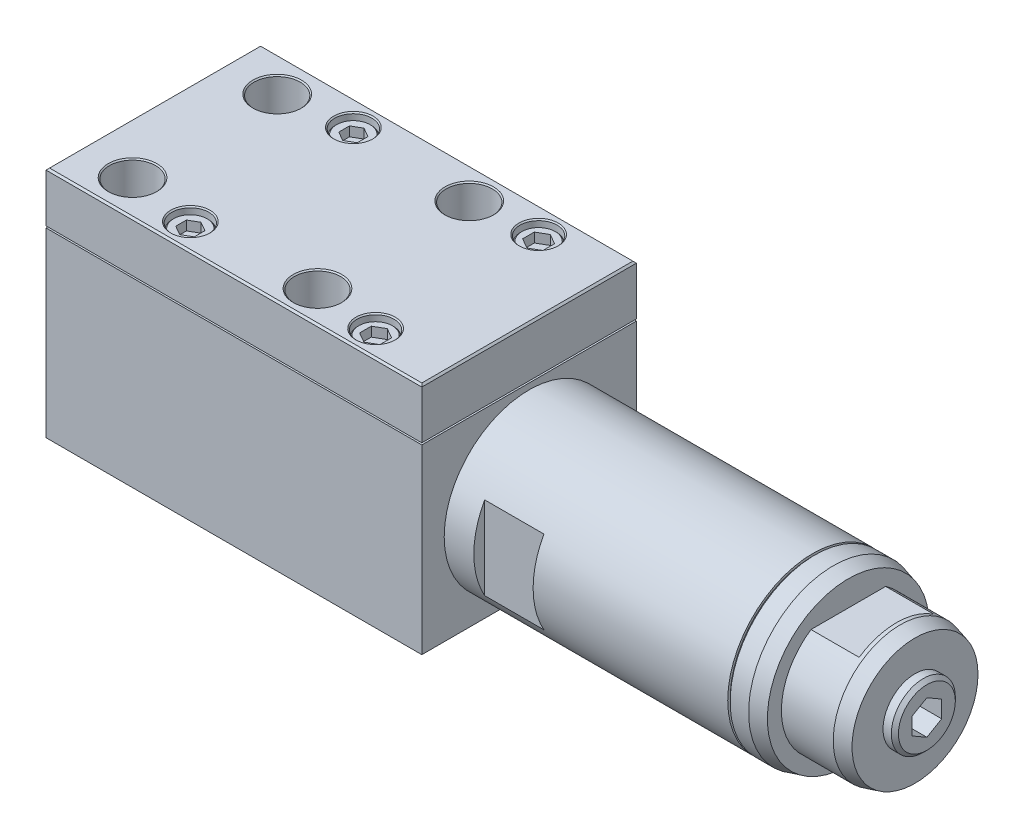
SolidWorks part; units mm, degrees
ref_plane "Front Plane" through (0, 0, 0) normal (0, 0, 1) x (1, 0, 0)
ref_plane "Top Plane" through (0, 0, 0) normal (0, 1, 0) x (1, 0, 0)
ref_plane "Right Plane" through (0, 0, 0) normal (1, 0, 0) x (0, 0, -1)
sketch "Sketch1" plane through (0, 0, 0) normal (0, 0, 1) x (1, 0, 0)
  line L0 (-81.5975, 50.038) -> (-81.5975, 0) construction
  line L1 (-84.1375, 50.038) -> (84.1375, 50.038)
  line L2 (-84.1375, 50.038) -> (-84.1375, 0)
  line L3 (-84.1375, 0) -> (84.1375, 0)
  line L4 (84.1375, 50.038) -> (84.1375, 0)
  line L5 (-1.0795, 50.038) -> (-1.0795, 0) construction
  line L6 (-81.5975, 38.9255) -> (-1.0795, 38.9255) construction
  dimension "D1" = 168.275
  dimension "D2" = 50.038
  dimension "D3" = 2.54
  dimension "D4" = 80.518
  dimension "D5" = 11.1125
sketch "Sketch2" plane through (0, 0, 0) normal (0, 0, 1) x (1, 0, 0)
  line L1 (-81.5975, 38.9255) -> (-1.0795, 38.9255)
  line L2 (-81.5975, 38.9255) -> (-81.5975, 0)
  line L3 (-81.5975, 0) -> (-1.0795, 0)
  line L4 (-1.0795, 38.9255) -> (-1.0795, 0)
extrude "Boss-Extrude1" add sketch "Sketch2" along normal mid plane 45.974
sketch "Sketch3" plane through (0, 38.9255, 0) normal (0, 1, 0) x (1, 0, 0)
  line L4 (-1.0795, 22.987) -> (-81.5975, 22.987)
  line L5 (-81.5975, 22.987) -> (-81.5975, -22.987)
  line L6 (-81.5975, -22.987) -> (-1.0795, -22.987)
  line L7 (-1.0795, -22.987) -> (-1.0795, 22.987)
  line L8 (-1.0795, 22.987) -> (-81.5975, 22.987)
  line L9 (-81.5975, 22.987) -> (-81.5975, -22.987)
  line L10 (-81.5975, -22.987) -> (-1.0795, -22.987)
  line L11 (-1.0795, -22.987) -> (-1.0795, 22.987)
  dimension "D1" = 0
extrude "Boss-Extrude2" add sketch "Sketch3" along normal up to vertex (11.1125 mm away) separate body up to point (-84.1375, 50.038, 0)
chamfer "Chamfer1" distance 0.381 angle 45 8 edges at (-41.3385, 38.9255, -22.987) (-81.5975, 38.9255, 0) (-41.3385, 38.9255, 22.987) (-1.0795, 38.9255, 0) (-41.3385, 50.038, 22.987) (-81.5975, 50.038, 0) (-41.3385, 50.038, -22.987) (-1.0795, 50.038, 0)
combine bodies "Combine1" operation type add bodies to combine 101 102
sketch "Sketch4" plane through (0, 50.038, 0) normal (0, 1, 0) x (1, 0, 0)
  line L0 (-70.5485, 15.494) -> (-70.5485, -15.494) construction
  line L1 (-30.1625, 16.256) -> (-30.1625, -16.256) construction
  line L2 (-70.5485, 0) -> (-30.1625, 0) construction
  line L3 (-81.5975, 0) -> (-1.0795, 0) construction
  line L4 (-1.4605, -22.606) -> (-1.4605, 22.606) construction
  circle A0 centre (-70.5485, 15.494) radius 4.953
  circle A1 centre (-30.1625, 16.256) radius 4.953
  circle A2 centre (-70.5485, -15.494) radius 4.953
  circle A3 centre (-30.1625, -16.256) radius 4.953
  dimension "D1" = 9.906
  dimension "D2" = 30.988
  dimension "D3" = 32.512
  dimension "D4" = 69.088
  dimension "D5" = 40.386
extrude "Cut-Extrude1" cut sketch "Sketch4" against normal offset from surface (28.038 mm away) 22 up to face at (-41.3385, 0, 0)
sketch "Sketch5" plane through (0, 50.038, 0) normal (0, 1, 0) x (1, 0, 0)
  line L0 (-56.1975, 17.4625) -> (-56.1975, -17.4625) construction
  line L1 (0, 0) -> (-56.1975, 0) construction
  line L2 (-81.5975, -22.987) -> (-81.5975, 22.987) construction
  circle A0 centre (-56.1975, 17.4625) radius 3.9687
  circle A1 centre (-16.51, 17.4625) radius 3.9688
  circle A2 centre (-56.1975, -17.4625) radius 3.9687
  circle A3 centre (-16.51, -17.4625) radius 3.9688
  dimension "D1" = 7.9375
  dimension "D2" = 34.925
  dimension "D3" = 39.6875
  dimension "D4" = 25.4
extrude "Cut-Extrude2" cut sketch "Sketch5" against normal blind 1.27
chamfer "Chamfer2" distance 0.254 angle 45 8 edges at (-70.5485, 50.038, 20.447) (-70.5485, 50.038, -10.541) (-16.51, 50.038, -13.4937) (-16.51, 50.038, 21.4313) (-30.1625, 50.038, 21.209) (-30.1625, 50.038, -11.303) (-56.1975, 50.038, 21.4313) (-56.1975, 50.038, -13.4937)
sketch "Sketch6" plane through (0, 48.768, 0) normal (0, 1, 0) x (1, 0, 0)
  circle A1 centre (-56.1975, 17.4625) radius 3.9688
  circle A2 centre (-56.1975, 17.4625) radius 3.9687
  circle A3 centre (-16.51, 17.4625) radius 3.9688
  circle A4 centre (-16.51, 17.4625) radius 3.9688
  circle A5 centre (-16.51, -17.4625) radius 3.9688
  circle A6 centre (-16.51, -17.4625) radius 3.9688
  circle A7 centre (-56.1975, -17.4625) radius 3.9688
  circle A8 centre (-56.1975, -17.4625) radius 3.9687
  dimension "D1" = 0
  dimension "D2" = 0
  dimension "D3" = 0
  dimension "D4" = 0
extrude "Cut-Extrude-Thin1" cut sketch "Sketch6" against normal blind 1.27 thin thin type one direction reverse wall 0.127
chamfer "Chamfer3" distance 0.254 angle 45 4 edges at (-12.6683, 48.768, -17.4625) (-12.6682, 48.768, 17.4625) (-52.3558, 48.768, 17.4625) (-52.3558, 48.768, -17.4625)
sketch "Sketch7" plane through (0, 48.768, 0) normal (0, 1, 0) x (1, 0, 0)
  line L1 (-56.1975, 19.7502) -> (-58.1787, 18.6063)
  line L2 (-58.1787, 18.6063) -> (-58.1787, 16.3187)
  line L3 (-58.1787, 16.3187) -> (-56.1975, 15.1748)
  line L4 (-56.1975, 15.1748) -> (-54.2163, 16.3187)
  line L5 (-54.2163, 16.3187) -> (-54.2163, 18.6063)
  line L6 (-54.2163, 18.6063) -> (-56.1975, 19.7502)
  line L7 (-56.1975, -15.1748) -> (-58.1787, -16.3187)
  line L8 (-58.1787, -16.3187) -> (-58.1787, -18.6063)
  line L9 (-58.1787, -18.6063) -> (-56.1975, -19.7502)
  line L10 (-56.1975, -19.7502) -> (-54.2163, -18.6063)
  line L11 (-54.2163, -18.6063) -> (-54.2163, -16.3187)
  line L12 (-54.2163, -16.3187) -> (-56.1975, -15.1748)
  line L13 (-16.51, -14.9588) -> (-18.6783, -16.2107)
  line L14 (-18.6783, -16.2107) -> (-18.6783, -18.7143)
  line L15 (-18.6783, -18.7143) -> (-16.51, -19.9662)
  line L16 (-16.51, -19.9662) -> (-14.3417, -18.7143)
  line L17 (-14.3417, -18.7143) -> (-14.3417, -16.2107)
  line L18 (-14.3417, -16.2107) -> (-16.51, -14.9588)
  line L19 (-16.51, 19.9662) -> (-18.6783, 18.7143)
  line L20 (-18.6783, 18.7143) -> (-18.6783, 16.2107)
  line L21 (-18.6783, 16.2107) -> (-16.51, 14.9588)
  line L22 (-16.51, 14.9588) -> (-14.3417, 16.2107)
  line L23 (-14.3417, 16.2107) -> (-14.3417, 18.7143)
  line L24 (-14.3417, 18.7143) -> (-16.51, 19.9662)
  circle A0 centre (-56.1975, 17.4625) radius 1.9812 construction
  circle A1 centre (-56.1975, -17.4625) radius 1.9812 construction
  circle A2 centre (-16.51, -17.4625) radius 2.1683 construction
  circle A3 centre (-16.51, 17.4625) radius 2.1683 construction
  dimension "D1" = 3.9624
extrude "Cut-Extrude3" cut sketch "Sketch7" against normal blind 2.032
sketch "Sketch8" plane through (0, 50.038, 0) normal (0, 1, 0) x (1, 0, 0)
  circle A0 centre (-70.5485, 15.494) radius 2.75
  circle A1 centre (-30.1625, 16.256) radius 2.75
  circle A2 centre (-30.1625, -16.256) radius 2.75
  circle A3 centre (-70.5485, -15.494) radius 2.75
  dimension "D1" = 5.5
extrude "Cut-Extrude4" cut sketch "Sketch8" against normal through all
sketch "Sketch9" plane through (0, 0, 0) normal (0, -1, 0) x (1, 0, 0)
  line L1 (-70.5485, -15.494) -> (-70.5485, 15.494) construction
  line L3 (-81.5975, 0) -> (-1.0795, 0) construction
  circle A0 centre (-48.9585, 10.414) radius 3.556
  circle A1 centre (-48.9585, -10.414) radius 3.556
  circle A2 centre (-57.8485, 0) radius 3.556
  circle A3 centre (-40.3225, 0) radius 3.556
  circle A4 centre (-37.5285, 15.494) radius 2.159 construction
  circle A5 centre (-70.5485, 15.494) radius 2.75 construction
  dimension "D1" = 7.112
  dimension "D2" = 4.318
  dimension "D8" = 25.908
  dimension "D3" = 33.02
  dimension "D4" = 21.59
  dimension "D5" = 12.7
  dimension "D6" = 30.226
  dimension "D7" = 5.08
extrude "Cut-Extrude5" cut sketch "Sketch9" against normal blind 2.54
sketch "Sketch10" plane through (0, 0, 0) normal (0, -1, 0) x (1, 0, 0)
  circle A0 centre (-37.5285, 15.494) radius 2.159 construction
  circle A1 centre (-37.5285, 15.494) radius 2.159
extrude "Cut-Extrude6" cut sketch "Sketch10" against normal blind 4
sketch "Sketch12" plane through (0, 2.54, 0) normal (0, -1, 0) x (1, 0, 0)
  circle A1 centre (-48.9585, 10.414) radius 3.556
  circle A2 centre (-48.9585, 10.414) radius 3.556
  circle A3 centre (-40.3225, 0) radius 3.556
  circle A4 centre (-40.3225, 0) radius 3.556
  circle A5 centre (-57.8485, 0) radius 3.556
  circle A6 centre (-57.8485, 0) radius 3.556
  circle A7 centre (-48.9585, -10.414) radius 3.556
  circle A8 centre (-48.9585, -10.414) radius 3.556
  dimension "D1" = 0
  dimension "D2" = 0
  dimension "D3" = 0
  dimension "D4" = 0
extrude "Cut-Extrude7" cut sketch "Sketch12" against normal through all draft 45
sketch "Sketch17" plane through (-1.0795, 0, 0) normal (1, 0, 0) x (0, 0, -1)
  line L4 (0, 50.038) -> (0, 0) construction
  line L8 (21.717, 1.27) -> (21.717, 37.6555)
  line L9 (21.717, 37.6555) -> (-21.717, 37.6555)
  line L10 (-21.717, 37.6555) -> (-21.717, 1.27)
  line L11 (-21.717, 1.27) -> (21.717, 1.27)
  line L12 (21.717, 1.27) -> (21.717, 37.6555) construction
  line L13 (21.717, 37.6555) -> (-21.717, 37.6555) construction
  line L14 (-21.717, 37.6555) -> (-21.717, 1.27) construction
  line L15 (-21.717, 1.27) -> (21.717, 1.27) construction
  circle A0 centre (0, 19.4627) radius 18.1928
  dimension "D1" = 1.27
extrude "Boss-Extrude4" add sketch "Sketch17" along normal up to vertex (85.217 mm away) up to point (84.1375, 0, 0)
sketch "Sketch13" plane through (-81.5975, 0, 0) normal (-1, 0, 0) x (0, 0, 1)
  circle A0 centre (0, 19.4627) radius 6.858
  circle A1 centre (0, 19.4627) radius 18.1928 construction
  dimension "D1" = 13.716
extrude "Boss-Extrude3" add sketch "Sketch13" along normal blind 2.54
chamfer "Chamfer4" distance 0.762 angle 45 1 edges at (-84.1375, 19.4627, 6.858)
sketch "Sketch14" plane through (-84.1375, 0, 0) normal (-1, 0, 0) x (0, 0, 1)
  line L1 (0, 23.1289) -> (-3.175, 21.2958)
  line L2 (-3.175, 21.2958) -> (-3.175, 17.6297)
  line L3 (-3.175, 17.6297) -> (0, 15.7966)
  line L4 (0, 15.7966) -> (3.175, 17.6297)
  line L5 (3.175, 17.6297) -> (3.175, 21.2958)
  line L6 (3.175, 21.2958) -> (0, 23.1289)
  circle A0 centre (0, 19.4627) radius 3.175 construction
  dimension "D1" = 6.35
extrude "Cut-Extrude8" cut sketch "Sketch14" against normal blind 5.08
sketch "Sketch15" plane through (-84.1375, 0, 0) normal (-1, 0, 0) x (0, 0, 1)
  circle A0 centre (0, 19.4627) radius 3.6662
extrude "Cut-Extrude9" cut sketch "Sketch15" against normal through all draft 45
sketch "Sketch18" plane through (84.1375, 0, 0) normal (1, 0, 0) x (0, 0, -1)
  circle A0 centre (0, 19.4627) radius 6.858
  dimension "D1" = 13.716
extrude "Cut-Extrude10" cut sketch "Sketch18" against normal blind 2.54 flip side to cut
sketch "Sketch19" plane through (84.1375, 0, 0) normal (1, 0, 0) x (0, 0, -1)
  line L6 (3.175, 21.2958) -> (0, 23.1289)
  line L7 (3.175, 17.6297) -> (3.175, 21.2958)
  line L8 (0, 15.7966) -> (3.175, 17.6297)
  line L9 (-3.175, 17.6297) -> (0, 15.7966)
  line L10 (-3.175, 21.2958) -> (-3.175, 17.6297)
  line L11 (0, 23.1289) -> (-3.175, 21.2958)
  line L12 (3.175, 21.2958) -> (0, 23.1289)
  line L13 (3.175, 17.6297) -> (3.175, 21.2958)
  line L14 (0, 15.7966) -> (3.175, 17.6297)
  line L15 (-3.175, 17.6297) -> (0, 15.7966)
  line L16 (-3.175, 21.2958) -> (-3.175, 17.6297)
  line L17 (0, 23.1289) -> (-3.175, 21.2958)
  dimension "D1" = 0
extrude "Cut-Extrude11" cut sketch "Sketch19" against normal blind 5.08
chamfer "Chamfer5" distance 0.762 angle 45 1 edges at (84.1375, 19.4627, -6.858)
sketch "Sketch20" plane through (0, 0, 0) normal (0, 0, 1) x (1, 0, 0)
  line L0 (81.5975, 32.9565) -> (78.4225, 33.8072)
  line L1 (81.5975, 1.27) -> (81.5975, 37.6555) construction
  line L2 (78.4225, 33.8072) -> (67.31, 33.8072)
  line L3 (67.31, 33.8072) -> (67.31, 36.8048)
  line L4 (67.31, 36.8048) -> (64.135, 37.6555)
  line L5 (81.5975, 37.6555) -> (-1.0795, 37.6555) construction
  line L6 (60.1726, 37.6555) -> (60.1726, 37.1475)
  line L7 (60.1726, 37.1475) -> (59.6646, 37.1475)
  line L8 (59.6646, 37.1475) -> (59.6646, 40.8305)
  line L9 (59.6646, 40.8305) -> (81.5975, 40.8305)
  line L10 (81.5975, 40.8305) -> (81.5975, 32.9565)
  line L11 (83.3755, 19.4627) -> (-1.0795, 19.4627) construction
  line L12 (83.3755, 12.6048) -> (83.3755, 26.3208) construction
  line L13 (60.1726, 37.6555) -> (64.135, 37.6555)
  line L14 (-1.0795, 50.038) -> (-1.0795, 0) construction
  dimension "D1" = 15
  dimension "D2" = 0.508
  dimension "D3" = 0.508
  dimension "D4" = 3.175
  dimension "D5" = 3.9624
  dimension "D6" = 26.9875
  dimension "D7" = 14.2875
  dimension "D8" = 3.175
revolve "Cut-Revolve1" cut sketch "Sketch20" angle 360 about L11
sketch "Sketch21" plane through (67.31, 0, 0) normal (1, 0, 0) x (0, 0, -1)
  line L0 (8.0003, 7.5565) -> (-8.0003, 7.5565)
  line L1 (-8.0003, 31.369) -> (8.0003, 31.369)
  circle A1 centre (0, 19.4627) radius 14.3445 construction
  arc A2 (8.0003, 31.369) -> (-8.0003, 31.369) centre (0, 19.4627) ccw
  circle A3 centre (0, 19.4627) radius 14.3445 construction
  arc A6 (-8.0003, 7.5565) -> (8.0003, 7.5565) centre (0, 19.4627) ccw
  circle A7 centre (0, 19.4627) radius 13.4937 construction
  dimension "D1" = 23.8125
extrude "Cut-Extrude12" cut sketch "Sketch21" along normal blind 10.3124
sketch "Sketch22" plane through (-1.0795, 0, 0) normal (1, 0, 0) x (0, 0, -1)
  line L0 (-15.875, 28.3487) -> (-15.875, 10.5768)
  line L1 (15.875, 28.3487) -> (15.875, 10.5768)
  circle A0 centre (0, 19.4627) radius 18.1928 construction
  arc A1 (-15.875, 28.3487) -> (-15.875, 10.5768) centre (0, 19.4627) ccw
  arc A2 (15.875, 10.5768) -> (15.875, 28.3487) centre (0, 19.4627) ccw
  dimension "D1" = 31.75
extrude "Cut-Extrude13" cut sketch "Sketch22" along normal blind 12.7 from offset 6.35
equation "\"D1@Cut-Extrude11\"=\"D1@Cut-Extrude8\""
equation "\"D1@Chamfer5\"=\"D1@Chamfer4\""
